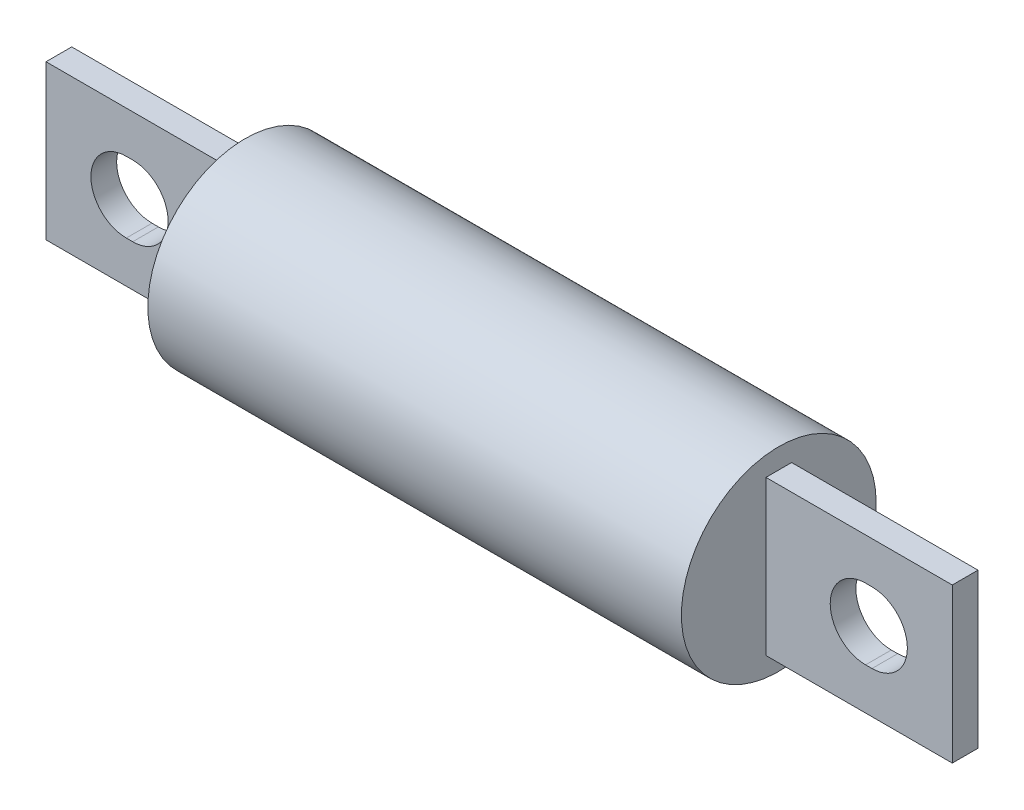
SolidWorks part; units mm, degrees
ref_plane "Front Plane" through (0, 0, 0) normal (0, 0, 1) x (1, 0, 0)
ref_plane "Top Plane" through (0, 0, 0) normal (0, 1, 0) x (1, 0, 0)
ref_plane "Right Plane" through (0, 0, 0) normal (1, 0, 0) x (0, 0, -1)
sketch "Sketch1" plane through (0, 0, 0) normal (1, 0, 0) x (0, 0, -1)
  circle A0 centre (0, 0) radius 12.0269
  dimension "D1" = 24.0538
extrude "Boss-Extrude1" add sketch "Sketch1" along normal blind 65.8876
sketch "Sketch2" plane through (65.8876, 0, 0) normal (1, 0, 0) x (0, 0, -1)
  line L1 (-1.5875, 9.525) -> (1.5875, 9.525)
  line L2 (-1.5875, 9.525) -> (-1.5875, -9.525)
  line L3 (-1.5875, -9.525) -> (1.5875, -9.525)
  line L4 (1.5875, 9.525) -> (1.5875, -9.525)
  line L5 (-1.5875, 9.525) -> (1.5875, -9.525) construction
  line L6 (-1.5875, -9.525) -> (1.5875, 9.525) construction
  point P0 (0, 0)
  dimension "D1" = 19.05
  dimension "D2" = 3.175
extrude "Boss-Extrude2" add sketch "Sketch2" along normal blind 23.0124 and the other way blind 88.9
sketch "Sketch5" plane through (0, 0, -1.5875) normal (0, 0, -1) x (-1, 0, 0)
  line L0 (-78.9813, 0) -> (-78.1939, 0) construction
  line L1 (-78.9813, 4.3688) -> (-78.1939, 4.3688)
  line L2 (-78.9813, -4.3688) -> (-78.1939, -4.3688)
  line L4 (-65.8876, -9.525) -> (-65.8876, 9.525) construction
  arc A0 (-78.9813, 4.3688) -> (-78.9813, -4.3688) centre (-78.9813, 0) ccw
  arc A1 (-78.1939, -4.3688) -> (-78.1939, 4.3688) centre (-78.1939, 0) ccw
  point P3 (-78.5876, 0)
  point P10 (-78.5876, -4.3688)
  dimension "D1" = 0.7874
  dimension "D2" = 8.7376
  dimension "D3" = 12.7
extrude "Cut-Extrude1" cut sketch "Sketch5" against normal blind 23.0124
sketch "Sketch6" plane through (0, 0, -1.5875) normal (0, 0, -1) x (-1, 0, 0)
  line L0 (13.095, 0) -> (12.305, 0) construction
  line L1 (13.095, -4.37) -> (12.305, -4.37)
  line L2 (13.095, 4.37) -> (12.305, 4.37)
  line L3 (0, -9.525) -> (0, 9.525) construction
  arc A0 (13.095, -4.37) -> (13.095, 4.37) centre (13.095, 0) ccw
  arc A1 (12.305, 4.37) -> (12.305, -4.37) centre (12.305, 0) ccw
  point P3 (12.7, 0)
  point P10 (12.7, -4.37)
  dimension "D1" = 12.7
  dimension "D2" = 0.79
  dimension "D3" = 8.74
extrude "Cut-Extrude2" cut sketch "Sketch6" against normal blind 23.0124
